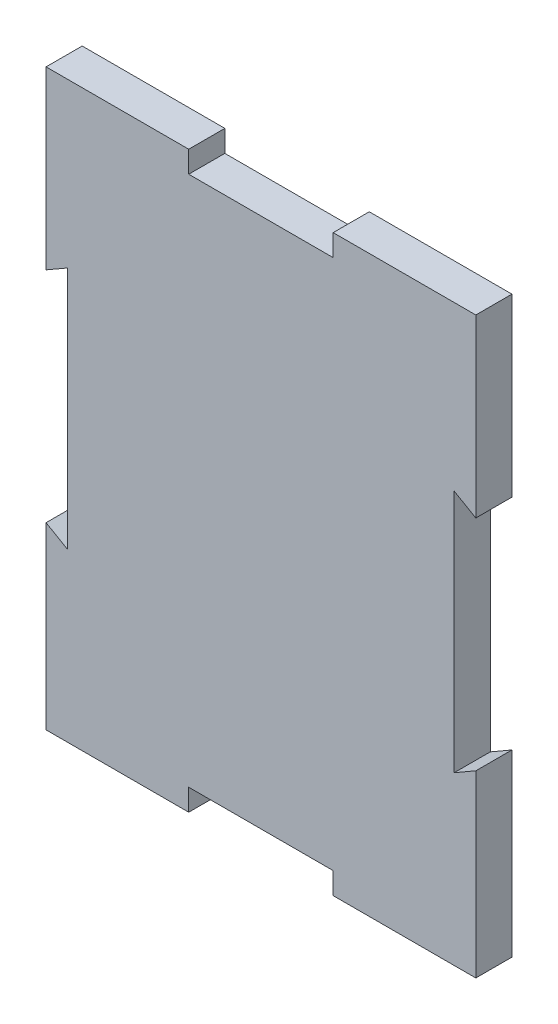
SolidWorks part; units mm, degrees
ref_plane "Front Plane" through (0, 0, 0) normal (1, 0, 0) x (0, 1, 0)
ref_plane "Top Plane" through (0, 0, 0) normal (0, 0, 1) x (0, 1, 0)
ref_plane "Right Plane" through (0, 0, 0) normal (0, 1, 0) x (-1, 0, 0)
sketch "Sketch4" plane through (0, 0, 0) normal (0, 0, 1) x (0, 1, 0)
  line L0 (0.25, -56) -> (-16.6375, -26.75)
  line L1 (-39.75, -29.75) -> (39.75, -29.75)
  line L2 (-39.75, -29.75) -> (-39.75, 29.75)
  line L3 (-39.75, 29.75) -> (39.75, 29.75)
  line L4 (39.75, -29.75) -> (39.75, 29.75)
  line L5 (-39.75, -29.75) -> (39.75, 29.75) construction
  line L6 (-39.75, 29.75) -> (39.75, -29.75) construction
  line L7 (-16.6375, -26.75) -> (17.1375, -26.75)
  line L8 (17.1375, -26.75) -> (0.25, -56)
  line L32 (-55, 0) -> (55, 0) construction
  line L33 (-16.6375, 26.75) -> (17.1375, 26.75)
  line L34 (17.1375, 26.75) -> (0.25, 56)
  line L35 (0.25, 56) -> (-16.6375, 26.75)
  line L36 (0, -55) -> (0, 55) construction
  line L37 (-42.75, -10) -> (-36.75, -10)
  line L38 (-42.75, -10) -> (-42.75, 10)
  line L39 (-42.75, 10) -> (-36.75, 10)
  line L40 (-36.75, -10) -> (-36.75, 10)
  line L41 (-42.75, -10) -> (-36.75, 10) construction
  line L42 (-42.75, 10) -> (-36.75, -10) construction
  line L43 (36.75, -10) -> (36.75, 10)
  line L44 (42.75, 10) -> (36.75, -10) construction
  line L45 (42.75, -10) -> (36.75, 10) construction
  line L46 (42.75, 10) -> (36.75, 10)
  line L47 (42.75, -10) -> (42.75, 10)
  line L48 (42.75, -10) -> (36.75, -10)
  circle A1 centre (0.25, -36.5) radius 9.75
  circle A9 centre (0.25, 36.5) radius 9.75
  point P0 (0, 0)
  point P18 (-39.75, 0)
  dimension "D3" = 20
  dimension "D4" = 19.5
  dimension "D5" = 79.5
  dimension "D1" = 6
  dimension "D2" = 40
  dimension "D6" = 59.5
  dimension "D8" = 3
extrude "Boss-Extrude1" add sketch "Sketch4" along normal blind 5
sketch "Sketch5" plane through (0, 0, 5) normal (0, 0, 1) x (1, 0, 0)
  line L1 (-26, -36) -> (26, -36)
  line L2 (-26, -36) -> (-26, 36)
  line L3 (-26, 36) -> (26, 36)
  line L4 (26, -36) -> (26, 36)
  line L5 (-26, -36) -> (26, 36) construction
  line L6 (-26, 36) -> (26, -36) construction
  point P0 (0, 0)
  dimension "D1" = 72
  dimension "D2" = 52
